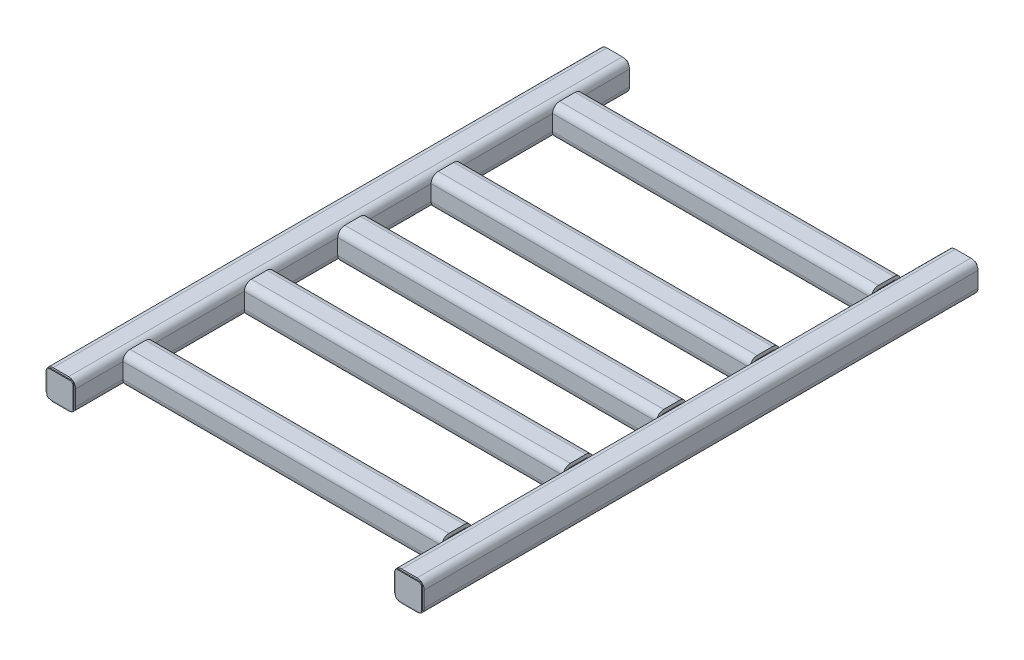
SolidWorks part; units mm, degrees
ref_plane "Front Plane" through (0, 0, 0) normal (0, 0, 1) x (1, 0, 0)
ref_plane "Top Plane" through (0, 0, 0) normal (0, 1, 0) x (1, 0, 0)
ref_plane "Right Plane" through (0, 0, 0) normal (1, 0, 0) x (0, 0, -1)
sketch3d "3DSketch1"
  line L0 (-186.6, 0, 230) -> (186.6, 0, 230)
  line L1 (-186.6, 0, -296.5) -> (-186.6, 0, 296.5)
  line L2 (-186.6, 0, -296.5) -> (186.6, 0, -296.5)
  line L3 (186.6, 0, -296.5) -> (186.6, 0, 296.5)
  line L4 (-186.6, 0, 296.5) -> (186.6, 0, 296.5)
  line L5 (-186.6, 0, -296.5) -> (186.6, 0, 296.5) construction
  line L6 (186.6, 0, -296.5) -> (-186.6, 0, 296.5) construction
  line L7 (-186.6, 0, 0) -> (186.6, 0, 0) construction
  line L8 (-186.6, 0, -230) -> (186.6, 0, -230)
  line L9 (0, 0, -296.5) -> (0, 0, -230) construction
  line L10 (0, 0, 230) -> (0, 0, 296.5) construction
  line L11 (-186.6, 0, -100) -> (186.6, 0, -100)
  line L12 (186.6, 0, 100) -> (-186.6, 0, 100)
  line L13 (0, 0, 0) -> (0, 0, -100) construction
  line L14 (0, 0, 100) -> (0, 0, 0) construction
  line L15 (186.6, 0, 0) -> (-186.6, 0, 0)
  point P0 (0, 0, 0)
  dimension "D1" = 593
  dimension "D2" = 373.2
  dimension "D3" = 230
  dimension "D5" = 100
  dimension "D7" = 130
other "Tube square TS32X32X4(1)"
ref_plane "Plane3" through (-186.6, 0, -296.5) normal (0, 0, 1) x (1, 0, 0)
sketch "Sketch113" plane through (-186.6, 0, -296.5) normal (0, 0, 1) x (1, 0, 0)
  line L0 (-8.28, -12.09) -> (8.28, -12.09)
  line L1 (-12.09, -8.28) -> (-12.09, 8.28)
  line L2 (8.28, 12.09) -> (-8.28, 12.09)
  line L3 (12.09, 8.28) -> (12.09, -8.28)
  line L4 (-8.28, -15.9) -> (8.28, -15.9)
  line L5 (-15.9, -8.28) -> (-15.9, 8.28)
  line L6 (8.28, 15.9) -> (-8.28, 15.9)
  line L7 (15.9, 8.28) -> (15.9, -8.28)
  line L8 (-15.9, 0) -> (-12.09, 0) construction
  line L9 (-12.09, 0) -> (12.09, 0) construction
  line L10 (12.09, 0) -> (15.9, 0) construction
  line L11 (0, 15.9) -> (0, 12.09) construction
  line L12 (0, 12.09) -> (0, -12.09) construction
  line L13 (0, -12.09) -> (0, -15.9) construction
  arc A0 (15.9, 8.28) -> (8.28, 15.9) centre (8.28, 8.28) ccw
  arc A1 (8.28, -15.9) -> (15.9, -8.28) centre (8.28, -8.28) ccw
  arc A2 (-15.9, -8.28) -> (-8.28, -15.9) centre (-8.28, -8.28) ccw
  arc A3 (-8.28, 15.9) -> (-15.9, 8.28) centre (-8.28, 8.28) ccw
  arc A4 (-8.28, 12.09) -> (-12.09, 8.28) centre (-8.28, 8.28) ccw
  arc A5 (12.09, 8.28) -> (8.28, 12.09) centre (8.28, 8.28) ccw
  arc A6 (8.28, -12.09) -> (12.09, -8.28) centre (8.28, -8.28) ccw
  arc A7 (-12.09, -8.28) -> (-8.28, -12.09) centre (-8.28, -8.28) ccw
  point P6 (-15.9, 15.9)
  point P33 (15.9, 15.9)
  point P34 (-15.9, -15.9)
  point P36 (15.9, -15.9)
  point P37 (0, 0)
  point P38 (0, 0)
  dimension "D1" = 7.62
  dimension "Thickness" = 3.81
  dimension "V_leg" = 31.8
  dimension "H_leg" = 31.8
other "End cap1" parameters "D1"=1, "D2"=3, "D3"=3, "D4"=0
